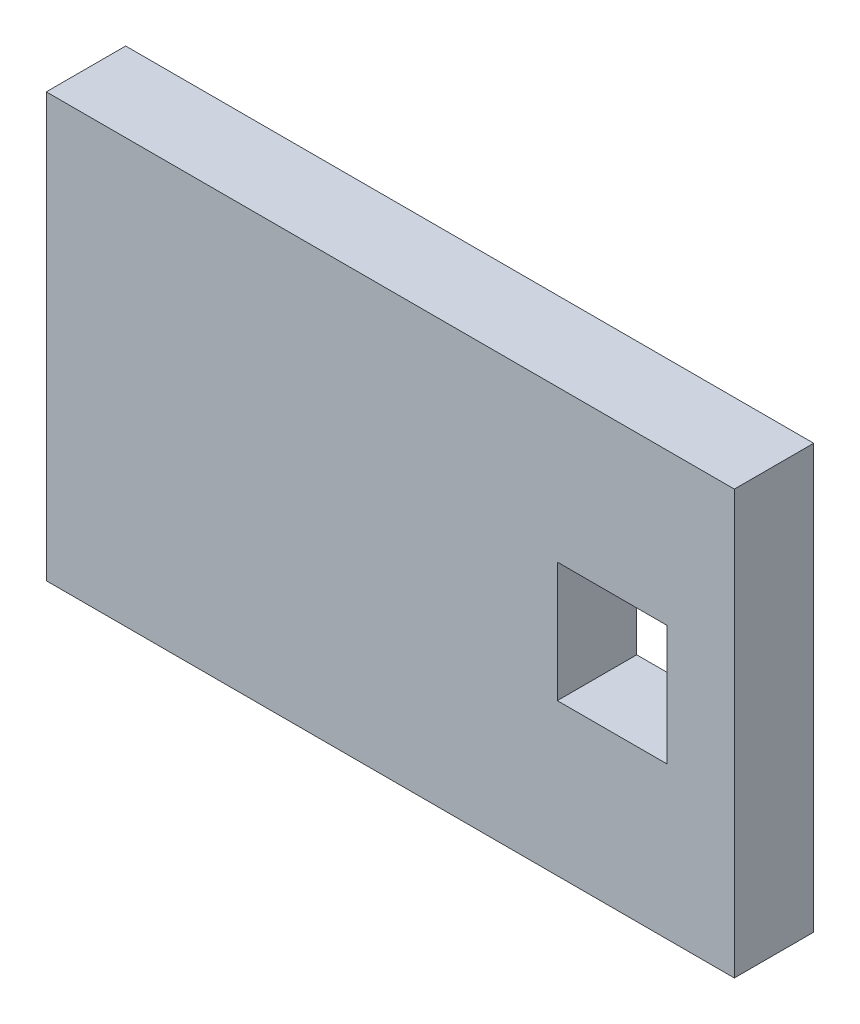
SolidWorks part; units mm, degrees
ref_plane "Ön Düzlem" through (0, 0, 0) normal (0, 0, 1) x (1, 0, 0)
ref_plane "Üst Düzlem" through (0, 0, 0) normal (0, 1, 0) x (1, 0, 0)
ref_plane "Sağ Düzlem" through (0, 0, 0) normal (1, 0, 0) x (0, 0, -1)
sketch "Çizim1" plane through (0, 0, 0) normal (0, 0, 1) x (1, 0, 0)
  line L1 (-13, -8) -> (13, -8)
  line L2 (-13, -8) -> (-13, 8)
  line L3 (-13, 8) -> (13, 8)
  line L4 (13, -8) -> (13, 8)
  line L5 (-13, -8) -> (13, 8) construction
  line L6 (-13, 8) -> (13, -8) construction
  circle A0 centre (8.3855, 0) radius 2.0723
  point P0 (0, 0)
  dimension "D1" = 26
  dimension "D2" = 16
extrude "Yükseklik-Ekstrüzyon1" add sketch "Çizim1" along normal blind 3
sketch "Çizim2" plane through (0, 0, 3) normal (0, 0, 1) x (1, 0, 0)
  line L1 (6.3116, -2.2676) -> (10.4594, -2.2676)
  line L2 (6.3116, -2.2676) -> (6.3116, 2.2676)
  line L3 (6.3116, 2.2676) -> (10.4594, 2.2676)
  line L4 (10.4594, -2.2676) -> (10.4594, 2.2676)
  line L5 (6.3116, -2.2676) -> (10.4594, 2.2676) construction
  line L6 (6.3116, 2.2676) -> (10.4594, -2.2676) construction
  point P0 (8.3855, 0)
extrude "Kes-Ekstrüzyon1" cut sketch "Çizim2" against normal blind 10
